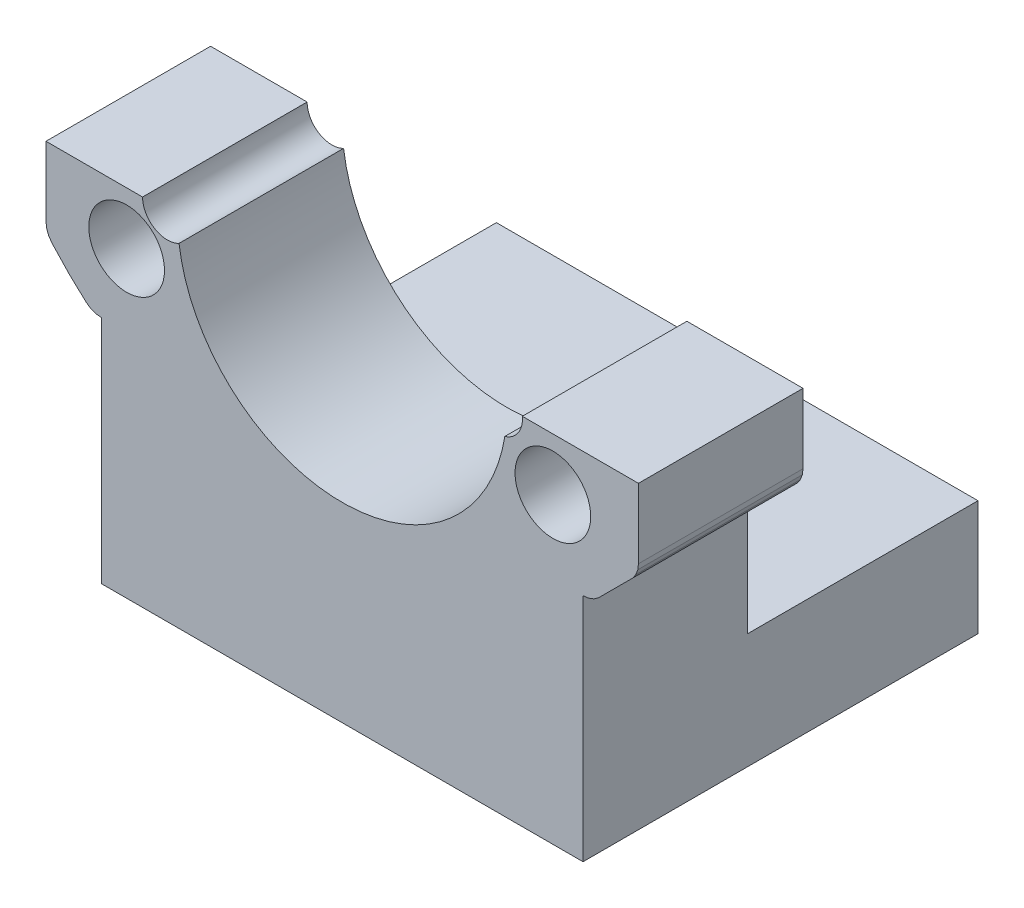
SolidWorks part; units mm, degrees
ref_plane "Front Plane" through (0, 0, 0) normal (0, 0, 1) x (1, 0, 0)
ref_plane "Top Plane" through (0, 0, 0) normal (0, 1, 0) x (1, 0, 0)
ref_plane "Right Plane" through (0, 0, 0) normal (1, 0, 0) x (0, 0, -1)
sketch "Sketch1" plane through (0, 0, 0) normal (0, 0, 1) x (1, 0, 0)
  line L1 (189.1991, 129.3361) -> (189.2194, 129.1684)
  line L2 (189.2194, 129.1684) -> (189.2766, 129.015)
  line L3 (189.2766, 129.015) -> (189.3751, 128.8705)
  line L4 (189.3751, 128.8705) -> (189.8798, 128.3332)
  line L5 (189.8798, 128.3332) -> (190.4171, 127.8285)
  line L6 (190.4171, 127.8285) -> (190.5582, 127.7318)
  line L7 (190.5582, 127.7318) -> (190.7157, 127.6726)
  line L8 (190.7157, 127.6726) -> (190.8827, 127.6526)
  line L9 (190.8827, 127.6526) -> (205.5156, 127.6526)
  line L10 (205.5156, 127.6526) -> (205.6833, 127.6728)
  line L11 (205.6833, 127.6728) -> (205.8401, 127.7318)
  line L12 (205.8401, 127.7318) -> (205.9812, 127.8285)
  line L13 (205.9812, 127.8285) -> (207.0232, 128.8705)
  line L14 (207.0232, 128.8705) -> (207.1185, 129.009)
  line L15 (207.1185, 129.009) -> (207.1789, 129.1684)
  line L16 (207.1789, 129.1684) -> (207.1991, 129.3361)
  line L17 (207.1991, 129.3361) -> (207.1991, 132.202)
  line L19 (207.1991, 132.202) -> (189.1991, 132.202)
  line L21 (189.1991, 132.202) -> (189.1991, 129.3361)
  dimension "D1" = 18
extrude "Face " add sketch "Sketch1" along normal blind 5
sketch "Sketch2" plane through (0, 127.6526, 0) normal (0, -1, 0) x (1, 0, 0)
  line L0 (55, 0) -> (-55, 0) construction
  line L1 (205.5156, 0) -> (190.8827, 0)
  line L2 (205.5156, 0) -> (205.5156, 5)
  line L3 (205.5156, 5) -> (190.8827, 5)
  line L4 (190.8827, 0) -> (190.8827, 5)
  line L5 (205.5156, 5) -> (205.5156, 0) construction
extrude "Boss-Extrude2" add sketch "Sketch2" along normal blind 7
sketch "Sketch3" plane through (0, 0, 0) normal (0, 0, -1) x (-1, 0, 0)
  line L0 (-205.5156, 127.6526) -> (-190.8827, 127.6526)
  line L1 (-190.8827, 127.6526) -> (-190.8827, 120.6526)
  line L2 (-190.8827, 120.6526) -> (-205.5156, 120.6526)
  line L3 (-205.5156, 120.6526) -> (-205.5156, 127.6526)
extrude "Boss-Extrude3" add sketch "Sketch3" along normal blind 7
sketch "Sketch4" plane through (0, 0, 5) normal (0, 0, 1) x (1, 0, 0)
  line L1 (207.1991, 132.202) -> (189.1991, 132.202) construction
  line L7 (190.4991, 129.852) -> (189.1991, 129.852) construction
  line L8 (189.1991, 132.202) -> (189.1991, 129.3361) construction
  line L9 (205.7491, 129.852) -> (207.1991, 129.852) construction
  line L10 (207.1991, 129.3361) -> (207.1991, 132.202) construction
  circle A0 centre (191.6491, 129.852) radius 1.15
  circle A1 centre (204.5991, 129.852) radius 1.15
  dimension "D5" = 2.3
  dimension "D1" = 1.3
  dimension "D2" = 1.45
  dimension "D3" = 2.35
extrude "Eye Holes" cut sketch "Sketch4" against normal up to next
sketch "Sketch5" plane through (0, 0, -7) normal (0, 0, -1) x (-1, 0, 0)
  line L0 (-205.5156, 124.1526) -> (-190.8827, 124.1526)
  line L1 (-205.5156, 127.6526) -> (-205.5156, 120.6526) construction
  line L2 (-190.8827, 120.6526) -> (-190.8827, 127.6526) construction
  line L3 (-190.8827, 124.1526) -> (-190.8827, 127.6526)
  line L4 (-190.8827, 127.6526) -> (-205.5156, 127.6526)
  line L5 (-205.5156, 127.6526) -> (-205.5156, 124.1526)
  dimension "D1" = 3.5
extrude "Seat" cut sketch "Sketch5" against normal blind 7
sketch "Sketch6" plane through (0, 132.202, 0) normal (0, 1, 0) x (1, 0, 0)
  line L1 (189.1991, 0) -> (207.1991, 0)
  line L2 (189.1991, 0) -> (189.1991, -5)
  line L3 (189.1991, -5) -> (207.1991, -5)
  line L4 (207.1991, 0) -> (207.1991, -5)
extrude "Boss-Extrude4" add sketch "Sketch6" along normal blind 3.5
sketch "Sketch7" plane through (0, 0, 5) normal (0, 0, 1) x (1, 0, 0)
  line L0 (189.1991, 135.702) -> (189.1817, 135.702) construction
  line L19 (189.1991, 135.702) -> (207.1991, 135.702) construction
  line L20 (207.1991, 135.702) -> (207.2067, 135.702) construction
  line L22 (189.1817, 135.702) -> (207.2067, 135.702)
  line L23 (189.1817, 135.702) -> (189.1817, 131.452)
  line L24 (189.1817, 131.452) -> (207.2067, 131.452)
  line L25 (207.2067, 135.702) -> (207.2067, 131.452)
  circle A1 centre (191.6491, 129.852) radius 1.15 construction
  dimension "D1" = 1.6
extrude "Top Hole" cut sketch "Sketch7" against normal through all
sketch "Sketch8" plane through (0, 0, 5) normal (0, 0, 1) x (1, 0, 0)
  line L1 (189.1991, 131.452) -> (207.1991, 131.452) construction
  circle A0 centre (198.1991, 131.452) radius 5.0037
extrude "Middle Hole" cut sketch "Sketch8" against normal through all both and the other way through all
sketch "Sketch10" plane through (0, 120.6526, 0) normal (0, -1, 0) x (1, 0, 0)
  line L0 (190.8827, 5) -> (190.8827, -7) construction
  line L1 (205.5156, -7) -> (205.5156, 5) construction
  circle A0 centre (193.3827, -3.3083) radius 1.15
  circle A1 centre (203.0156, -3.3083) radius 1.15
  dimension "D3" = 2.5
  dimension "D1" = 2.3
  dimension "D2" = 2.5
sketch "Sketch11" plane through (0, 0, 5) normal (0, 0, 1) x (1, 0, 0)
  line L5 (189.1991, 131.452) -> (193.1954, 131.452) construction
  circle A0 centre (192.8869, 131.452) radius 0.7544
  circle A1 centre (202.92, 131.3773) radius 0.7544
extrude "Cut-Extrude9" cut sketch "Sketch11" against normal through all
